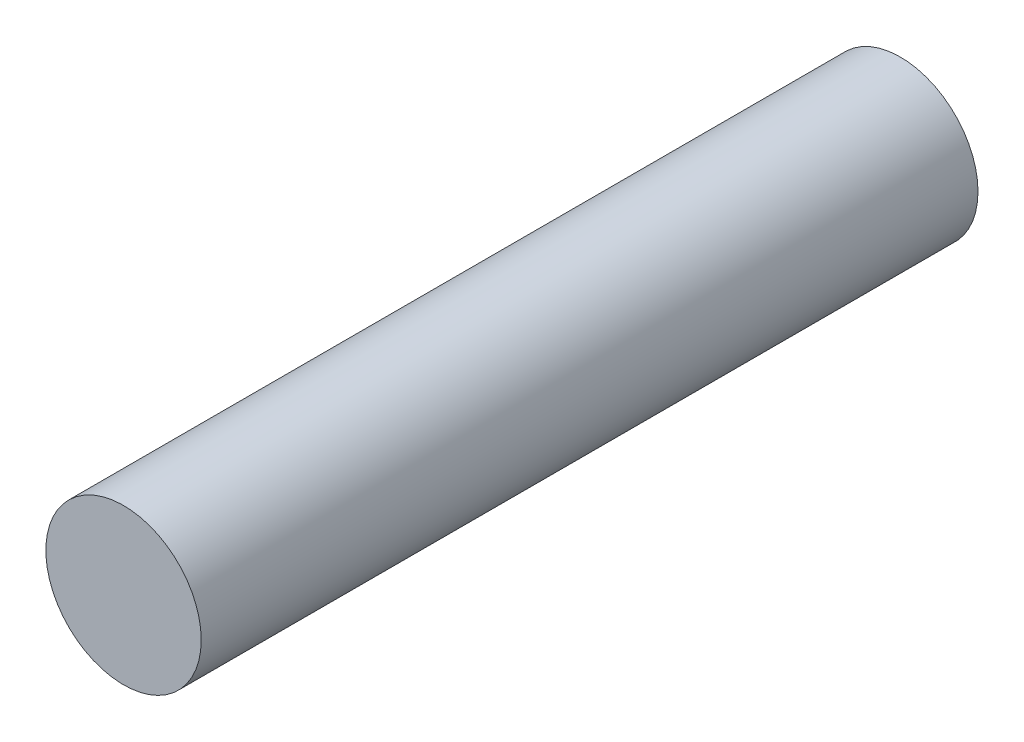
SolidWorks part; units mm, degrees
ref_plane "Front Plane" through (0, 0, 0) normal (0, 0, 1) x (1, 0, 0)
ref_plane "Top Plane" through (0, 0, 0) normal (0, 1, 0) x (1, 0, 0)
ref_plane "Right Plane" through (0, 0, 0) normal (1, 0, 0) x (0, 0, -1)
sketch "Sketch1" plane through (0, 0, 0) normal (0, 0, 1) x (1, 0, 0)
  circle A2 centre (0, 0) radius 1
  dimension "D1" = 2
extrude "Boss-Extrude2" add sketch "Sketch1" along normal mid plane 10
